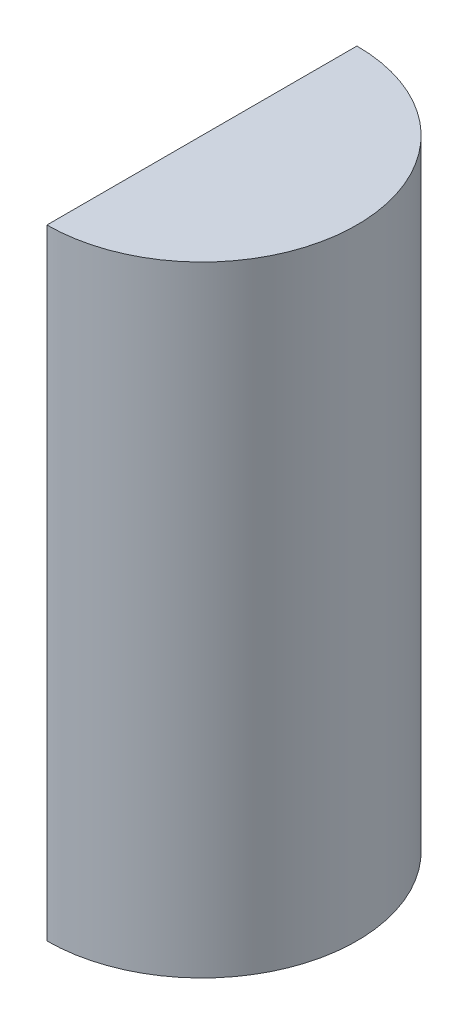
SolidWorks part; units mm, degrees
ref_plane "Front Plane" through (0, 0, 0) normal (0, 0, 1) x (1, 0, 0)
ref_plane "Top Plane" through (0, 0, 0) normal (0, 1, 0) x (1, 0, 0)
ref_plane "Right Plane" through (0, 0, 0) normal (1, 0, 0) x (0, 0, -1)
sketch "Sketch1" plane through (0, 0, 0) normal (0, 1, 0) x (1, 0, 0)
  line L0 (0, 19.05) -> (0, -19.05)
  arc A0 (0, 19.05) -> (0, -19.05) centre (0, 0) cw
extrude "Boss-Extrude1" add sketch "Sketch1" along normal blind 76.2
